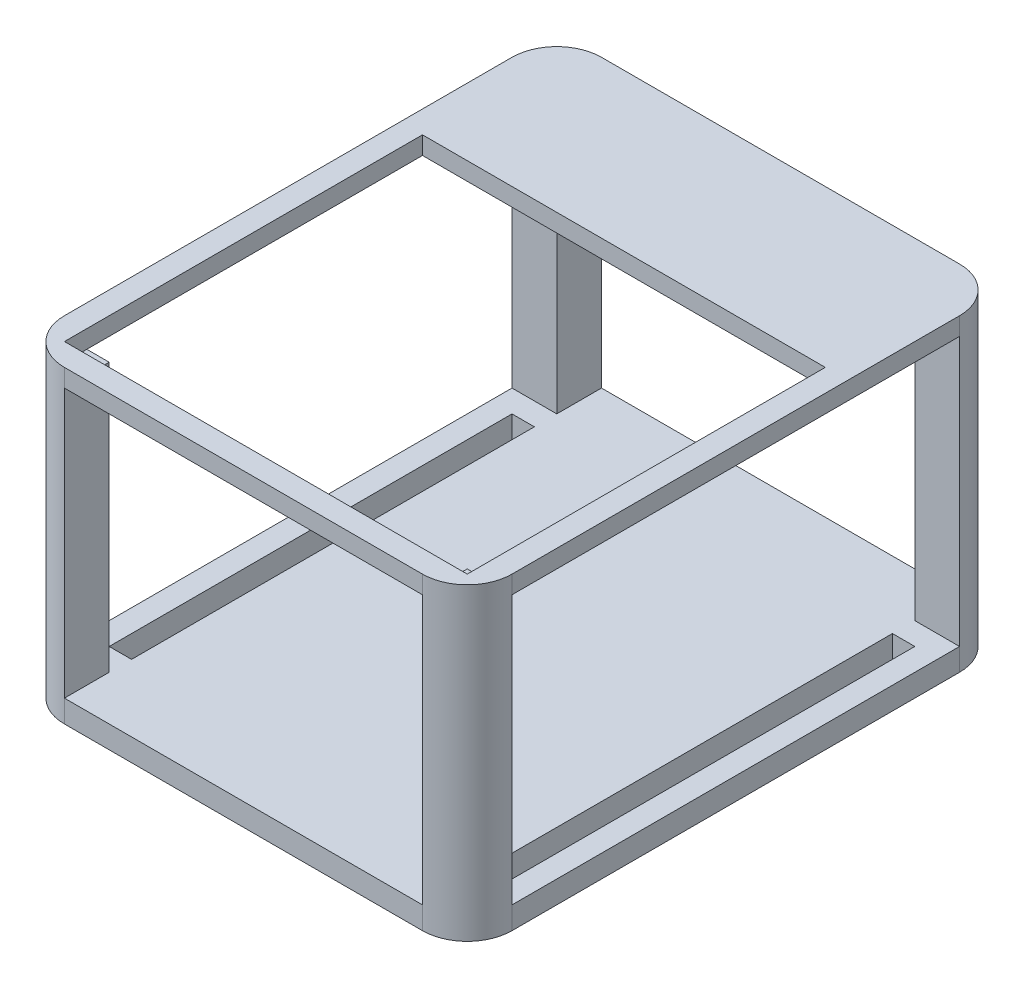
SolidWorks part; units mm, degrees
ref_plane "Front Plane" through (0, 0, 0) normal (0, 0, 1) x (1, 0, 0)
ref_plane "Top Plane" through (0, 0, 0) normal (0, 1, 0) x (1, 0, 0)
ref_plane "Right Plane" through (0, 0, 0) normal (1, 0, 0) x (0, 0, -1)
sketch "Sketch1" plane through (0, 0, 0) normal (0, 1, 0) x (1, 0, 0)
  line L5 (-40, 60) -> (40, 60)
  line L6 (-50, 50) -> (-50, -50)
  line L7 (-40, -60) -> (40, -60)
  line L8 (50, 50) -> (50, -50)
  arc A0 (50, 50) -> (40, 60) centre (40, 50) ccw
  arc A1 (40, -60) -> (50, -50) centre (40, -50) ccw
  arc A2 (-50, -50) -> (-40, -60) centre (-40, -50) ccw
  arc A3 (-50, 50) -> (-40, 60) centre (-40, 50) cw
  point P7 (50, 60)
  point P10 (50, -60)
  point P13 (-50, -60)
  dimension "D5" = 10
  dimension "D1" = 100
  dimension "D2" = 120
  dimension "D3" = 60
  dimension "D4" = 50
extrude "Boss-Extrude1" add sketch "Sketch1" along normal blind 5
sketch "Sketch2" plane through (0, 5, 0) normal (0, 1, 0) x (1, 0, 0)
  line L0 (-40, -60) -> (40, -60) construction
  line L1 (-45, 45) -> (-40, 45)
  line L2 (-45, 45) -> (-45, -45)
  line L3 (-45, -45) -> (-40, -45)
  line L4 (-40, 45) -> (-40, -45)
  line L5 (40, 45) -> (45, 45)
  line L6 (40, 45) -> (40, -45)
  line L7 (40, -45) -> (45, -45)
  line L8 (45, 45) -> (45, -45)
  dimension "D1" = 40
  dimension "D2" = 40
  dimension "D3" = 5
  dimension "D4" = 90
  dimension "D5" = 90
  dimension "D6" = 5
  dimension "D7" = 15
  dimension "D8" = 15
extrude "Cut-Extrude1" cut sketch "Sketch2" against normal through all
sketch "Sketch3" plane through (0, 5, 0) normal (0, 1, 0) x (1, 0, 0)
  line L1 (-50, 50) -> (-40, 50)
  line L4 (-40, 50) -> (-40, 60)
  line L8 (40, 60) -> (40, 50)
  line L9 (40, 50) -> (50, 50)
  line L12 (-50, -50) -> (-40, -50)
  line L15 (-40, -50) -> (-40, -60)
  line L17 (50, -50) -> (40, -50)
  line L20 (40, -50) -> (40, -60)
  arc A0 (-40, 60) -> (-50, 50) centre (-40, 50) ccw construction
  arc A1 (-40, 60) -> (-50, 50) centre (-40, 50) ccw
  arc A2 (40, -60) -> (50, -50) centre (40, -50) ccw construction
  arc A3 (-50, -50) -> (-40, -60) centre (-40, -50) ccw construction
  arc A4 (50, 50) -> (40, 60) centre (40, 50) ccw construction
  arc A5 (40, -60) -> (50, -50) centre (40, -50) ccw
  arc A6 (-50, -50) -> (-40, -60) centre (-40, -50) ccw
  arc A7 (50, 50) -> (40, 60) centre (40, 50) ccw
  dimension "D1" = 10
  dimension "D2" = 10
  dimension "D5" = 10
  dimension "D6" = 10
  dimension "D7" = 10
  dimension "D8" = 10
extrude "Boss-Extrude3" add sketch "Sketch3" along normal blind 60
sketch "Sketch4" plane through (0, 65, 0) normal (0, 1, 0) x (1, 0, 0)
  line L0 (50, -50) -> (50, 50) construction
  line L1 (-40, -60) -> (40, -60) construction
  line L2 (-50, 50) -> (-50, -50) construction
  line L3 (40, 60) -> (-40, 60) construction
  line L4 (50, -50) -> (50, 50)
  line L5 (-40, -60) -> (40, -60)
  line L6 (-50, 50) -> (-50, -50)
  line L7 (40, 60) -> (-40, 60)
  arc A0 (50, 50) -> (40, 60) centre (40, 50) ccw construction
  arc A1 (40, -60) -> (50, -50) centre (40, -50) ccw construction
  arc A2 (-50, -50) -> (-40, -60) centre (-40, -50) ccw construction
  arc A3 (-40, 60) -> (-50, 50) centre (-40, 50) ccw construction
  arc A4 (50, 50) -> (40, 60) centre (40, 50) ccw
  arc A5 (40, -60) -> (50, -50) centre (40, -50) ccw
  arc A6 (-50, -50) -> (-40, -60) centre (-40, -50) ccw
  arc A7 (-40, 60) -> (-50, 50) centre (-40, 50) ccw
extrude "Boss-Extrude4" add sketch "Sketch4" along normal blind 4
sketch "Sketch5" plane through (0, 69, 0) normal (0, 1, 0) x (1, 0, 0)
  line L0 (-40, -60) -> (40, -60) construction
  line L1 (-45, 25) -> (45, 25)
  line L2 (-45, 25) -> (-45, -55)
  line L3 (-45, -55) -> (45, -55)
  line L4 (45, 25) -> (45, -55)
  line L5 (-50, 50) -> (-50, -50) construction
  dimension "D1" = 90
  dimension "D2" = 80
  dimension "D3" = 5
  dimension "D4" = 5
extrude "Cut-Extrude2" cut sketch "Sketch5" against normal blind 4
